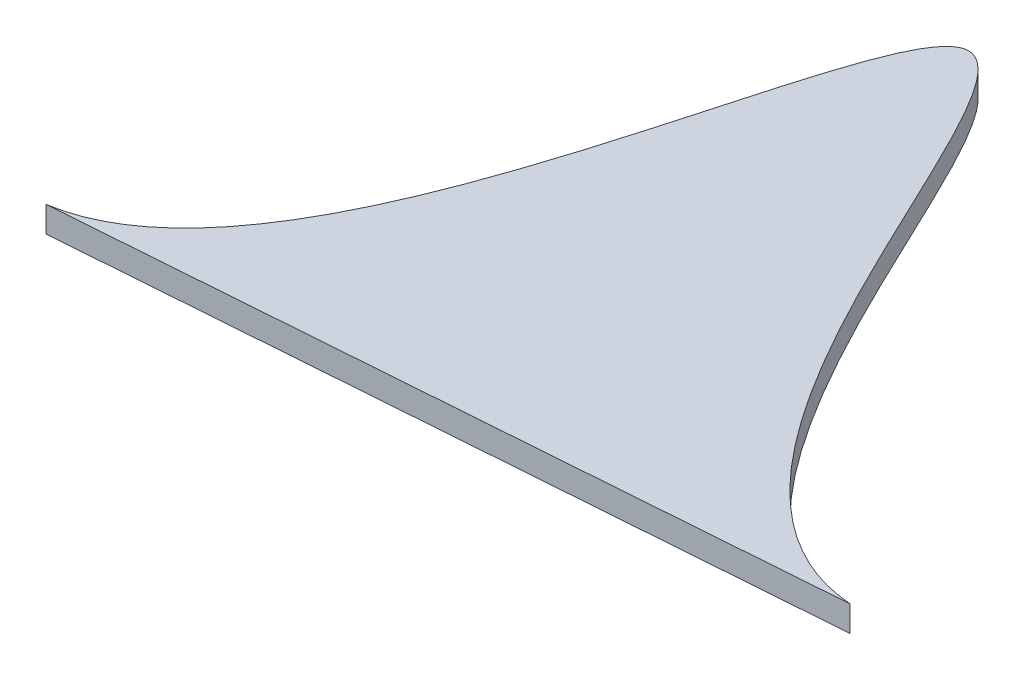
SolidWorks part; units mm, degrees
ref_plane "Ön Düzlem" through (0, 0, 0) normal (0, 0, 1) x (1, 0, 0)
ref_plane "Üst Düzlem" through (0, 0, 0) normal (0, 1, 0) x (1, 0, 0)
ref_plane "Sağ Düzlem" through (0, 0, 0) normal (1, 0, 0) x (0, 0, -1)
sketch "Sketch1" plane through (0, 0, 0) normal (0, 1, 0) x (1, 0, 0)
  line L0 (0, 0) -> (150, 0) construction
  line L1 (0, 0) -> (150, 11.2522) construction
  line L2 (0, 0) -> (150, 11.2522)
  spline S0 degree 3 poles (0, 0) (47.328, -0.1783) (58.4104, 224.5364) (105.9753, 14.3197) (150, 11.2522) knots 0 0 0 0 0.503859 1 1 1 1
  point P5 (150.08, 13.1233)
  point P7 (110.723, 56.1292)
  point P9 (38.1293, 56.8409)
  point P10 (124.0081, 25.5259)
  point P11 (35.9942, 30.7451)
  dimension "D1" = 4.29
  dimension "D2" = 150
  dimension "D3" = 150
extrude "Boss-Extrude1" add sketch "Sketch1" along normal mid plane 5
sketch "Sketch2" plane through (0, 0, 0) normal (0.0748, 0, 0.9972) x (0.9972, 0, -0.0748)
  line L0 (4.5223, 2.5) -> (150.4215, 2.5) construction
  line L1 (77.4719, -2.5) -> (77.4719, -7.5) construction
  line L2 (4.5223, -2.5) -> (150.4215, -2.5) construction
  circle A0 centre (77.4719, -7.5) radius 4
  dimension "D1" = 8
  dimension "D3" = 10
